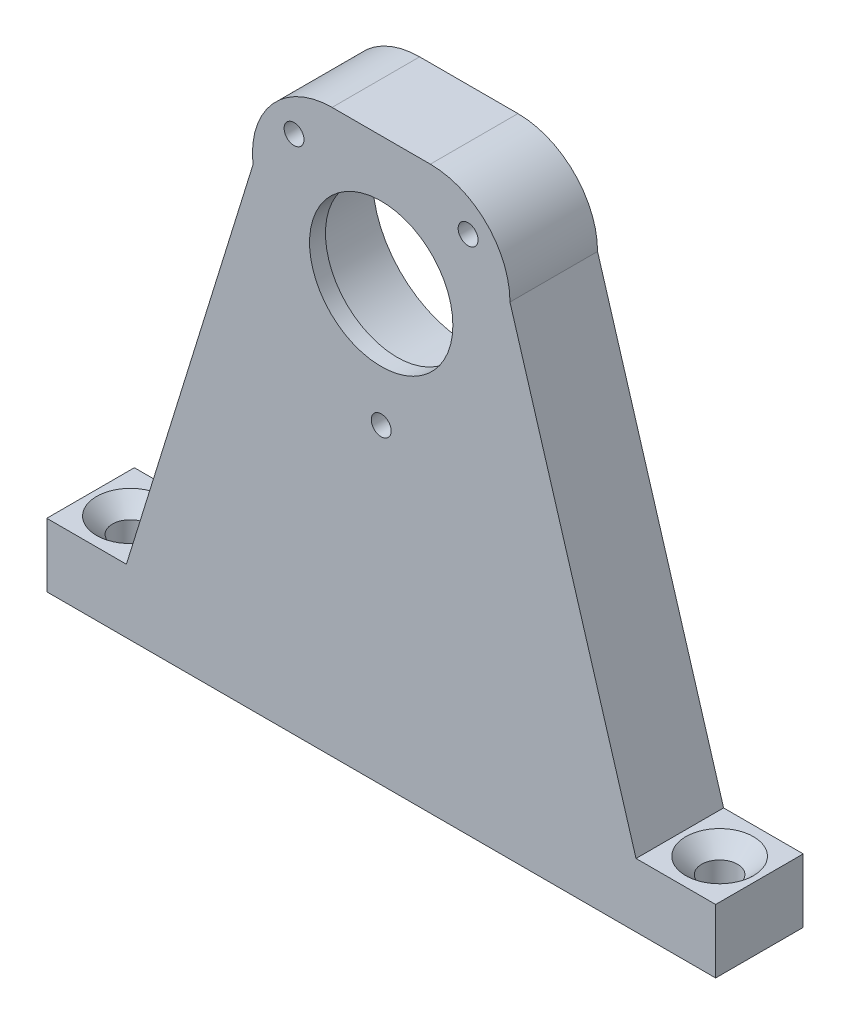
SolidWorks part; units mm, degrees
material "PET"
ref_plane "Piano frontale" through (0, 0, 0) normal (0, 0, 1) x (1, 0, 0)
ref_plane "Piano superiore" through (0, 0, 0) normal (0, 1, 0) x (1, 0, 0)
ref_plane "Piano destro" through (0, 0, 0) normal (1, 0, 0) x (0, 0, -1)
sketch "Schizzo1" plane through (0, 0, 0) normal (0, 0, 1) x (1, 0, 0)
  line L0 (-16.1, 0) -> (0, 0) construction
  line L1 (-6.1713, 16.1) -> (6.1713, 16.1)
  line L3 (-17, -54.5) -> (17, -54.5)
  line L5 (0, 0) -> (16.1, 0) construction
  line L7 (-17, -54.5) -> (-42, -54.5)
  line L11 (17, -54.5) -> (42, -54.5)
  line L16 (42, -54.5) -> (42, -46.5)
  line L18 (-42, -54.5) -> (-42, -46.5)
  line L20 (42, -46.5) -> (32, -46.5)
  line L21 (32, -46.5) -> (16.1713, 6.1)
  line L22 (-42, -46.5) -> (-32, -46.5)
  line L23 (-32, -46.5) -> (-16.1, 4.9079)
  circle A0 centre (0, 0) radius 12.1
  arc A1 (16.1713, 6.1) -> (6.1713, 16.1) centre (6.1713, 6.1) ccw
  arc A2 (-16.1, 4.9079) -> (-6.1713, 16.1) centre (-6.1713, 6.1) cw
  point P13 (0, -54.5)
  point P14 (0, 16.1)
  dimension "D1" = 24.2
  dimension "D3" = 25
  dimension "D4" = 10
  dimension "D7" = 8
  dimension "D2" = 16.1
  dimension "D5" = 54.5
  dimension "D6" = 34
  dimension "D8" = 10
  dimension "D9" = 10
extrude "Estrusione-Estrusione1" add sketch "Schizzo1" along normal blind 11
sketch "Schizzo2" plane through (0, 0, 11) normal (0, 0, 1) x (1, 0, 0)
  circle A0 centre (0, 0) radius 9
  circle A1 centre (0, 0) radius 12.1
  dimension "D1" = 18
extrude "Estrusione-Estrusione2" add sketch "Schizzo2" against normal blind 2
sketch "Schizzo3" plane through (0, -46.5, 0) normal (0, 1, 0) x (1, 0, 0)
  line L0 (32, -11) -> (42, 0) construction
  line L1 (-42, -11) -> (-32, 0) construction
  circle A0 centre (37, -5.5) radius 2.25
  circle A1 centre (-37, -5.5) radius 2.25
  dimension "D1" = 4.5
extrude "Taglio-Estrusione1" cut sketch "Schizzo3" against normal through all
chamfer "Smusso1" distance 2 angle 45 2 edges at (-37, -46.5, 7.75) (37, -46.5, 7.75)
sketch "Schizzo4" plane through (0, 0, 0) normal (0, 0, -1) x (-1, 0, 0)
  line L0 (-8.5791, 8.5329) -> (-13.2424, 13.1711) construction
  line L1 (8.6056, 8.5061) -> (13.2834, 13.1299) construction
  line L2 (0, -12.1) -> (0, -18.6772) construction
  arc A0 (-6.1713, 16.1) -> (-16.1713, 6.1) centre (-6.1713, 6.1) ccw construction
  arc A1 (16.1, 4.9079) -> (6.1713, 16.1) centre (6.1713, 6.1) ccw construction
  circle A2 centre (0, 0) radius 12.1 construction
  circle A3 centre (0, 0) radius 12.1 construction
  circle A4 centre (-10.9107, 10.852) radius 1.25
  circle A5 centre (10.9445, 10.818) radius 1.25
  circle A6 centre (0, -15.3886) radius 1.25
  dimension "D1" = 2.5
extrude "Taglio-Estrusione2" cut sketch "Schizzo4" against normal through all
